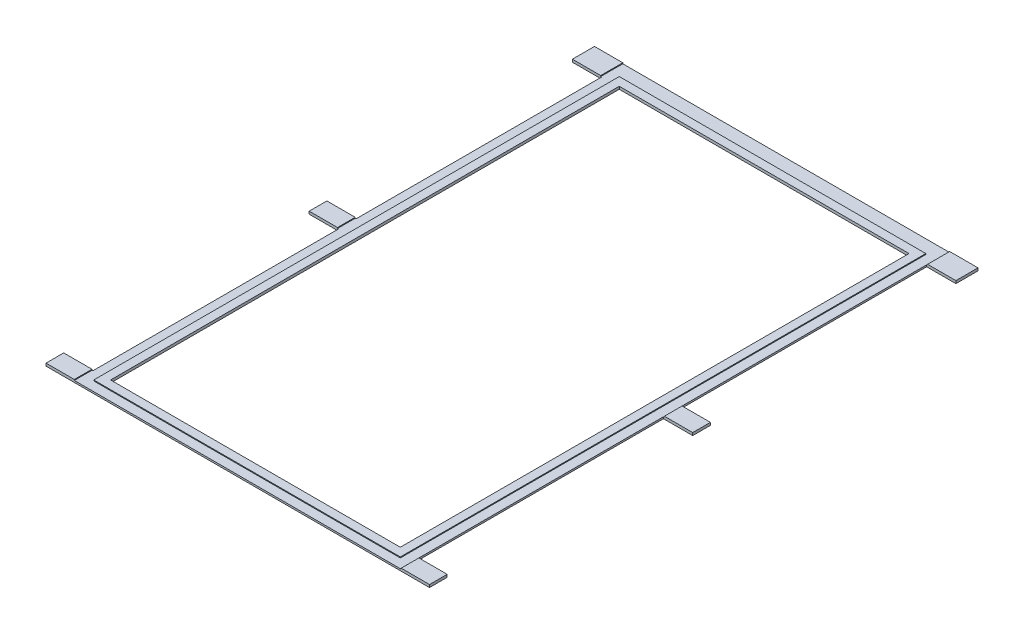
SolidWorks part; units mm, degrees
ref_plane "Front Plane" through (0, 0, 0) normal (0, 0, 1) x (1, 0, 0)
ref_plane "Top Plane" through (0, 0, 0) normal (0, 1, 0) x (1, 0, 0)
ref_plane "Right Plane" through (0, 0, 0) normal (1, 0, 0) x (0, 0, -1)
sketch "Sketch1" plane through (0, 0, 0) normal (0, 1, 0) x (1, 0, 0)
  line L0 (-433.5, 620) -> (433.5, 620)
  line L1 (-367.5, 620) -> (367.5, 620) construction
  line L2 (-367.5, 620) -> (-367.5, -620) construction
  line L3 (-367.5, -620) -> (367.5, -620) construction
  line L4 (367.5, 620) -> (367.5, -620) construction
  line L5 (-367.5, 620) -> (367.5, -620) construction
  line L6 (-367.5, -620) -> (367.5, 620) construction
  line L7 (-327.5, 570) -> (327.5, 570)
  line L8 (-327.5, 570) -> (-327.5, -580)
  line L9 (-327.5, -580) -> (327.5, -580)
  line L10 (327.5, 570) -> (327.5, -580)
  line L11 (-327.5, 570) -> (327.5, -580) construction
  line L12 (-327.5, -580) -> (327.5, 570) construction
  line L13 (433.5, 620) -> (433.5, 570)
  line L14 (433.5, 570) -> (367.5, 570)
  line L15 (367.5, 570) -> (367.5, 15)
  line L16 (367.5, 15) -> (433.5, 15)
  line L17 (433.5, 15) -> (433.5, -25)
  line L18 (433.5, -25) -> (367.5, -25)
  line L19 (367.5, -25) -> (367.5, -580)
  line L20 (367.5, -580) -> (433.5, -580)
  line L21 (433.5, -580) -> (433.5, -620)
  line L22 (433.5, -620) -> (-433.5, -620)
  line L23 (-433.5, -620) -> (-433.5, -580)
  line L24 (-433.5, -580) -> (-367.5, -580)
  line L25 (-367.5, -580) -> (-367.5, -25)
  line L26 (-367.5, -25) -> (-433.5, -25)
  line L27 (-433.5, -25) -> (-433.5, 15)
  line L28 (-433.5, 15) -> (-367.5, 15)
  line L29 (-367.5, 15) -> (-367.5, 570)
  line L30 (-367.5, 570) -> (-433.5, 570)
  line L31 (-433.5, 570) -> (-433.5, 620)
  point P0 (0, 0)
  point P6 (0, -5)
  dimension "D1" = 1150
  dimension "D2" = 655
  dimension "D3" = 735
  dimension "D4" = 1240
  dimension "D5" = 40
  dimension "D6" = 66
  dimension "D7" = 66
  dimension "D8" = 50
  dimension "D9" = 40
  dimension "D10" = 555
extrude "Boss-Extrude1" add sketch "Sketch1" along normal blind 6
sketch "Sketch2" plane through (0, 6, 0) normal (0, 1, 0) x (1, 0, 0)
  line L0 (-367.5, 570) -> (-367.5, 15) construction
  line L1 (-346.5, 589) -> (346.5, 589)
  line L2 (-346.5, 589) -> (-346.5, -599)
  line L3 (-346.5, -599) -> (346.5, -599)
  line L4 (346.5, 589) -> (346.5, -599)
  line L5 (-346.5, 589) -> (346.5, -599) construction
  line L6 (-346.5, -599) -> (346.5, 589) construction
  line L7 (-369.5, 630) -> (369.5, 630)
  line L8 (-369.5, 630) -> (-369.5, -630)
  line L9 (-369.5, -630) -> (369.5, -630)
  line L10 (369.5, 630) -> (369.5, -630)
  line L11 (-369.5, 630) -> (369.5, -630) construction
  line L12 (-369.5, -630) -> (369.5, 630) construction
  line L13 (367.5, 15) -> (367.5, 570) construction
  line L14 (-433.5, -620) -> (433.5, -620) construction
  line L15 (433.5, 620) -> (-433.5, 620) construction
  line L16 (327.5, 570) -> (-327.5, 570) construction
  line L17 (-327.5, 570) -> (-327.5, -580) construction
  line L18 (327.5, -580) -> (327.5, 570) construction
  line L19 (-327.5, -580) -> (327.5, -580) construction
  point P0 (0, -5)
  point P5 (0, 0)
  dimension "D1" = 2
  dimension "D2" = 2
  dimension "D3" = 10
  dimension "D4" = 10
  dimension "D5" = 19
  dimension "D6" = 19
  dimension "D7" = 19
  dimension "D8" = 19
extrude "Cut-Extrude1" cut sketch "Sketch2" against normal blind 2
